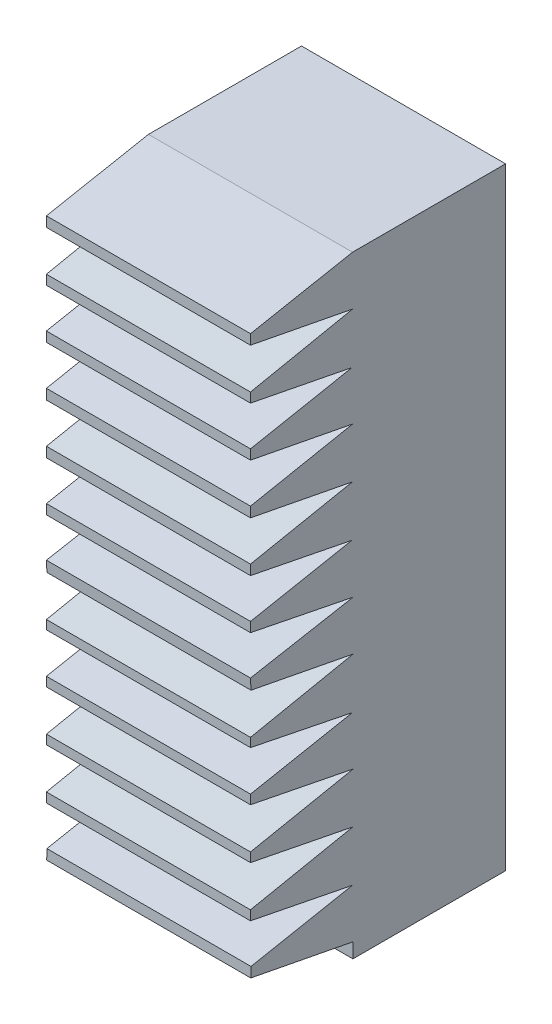
SolidWorks part; units mm, degrees
ref_plane "Alzado" through (0, 0, 0) normal (0, 0, 1) x (1, 0, 0)
ref_plane "Planta" through (0, 0, 0) normal (0, 1, 0) x (1, 0, 0)
ref_plane "Vista lateral" through (0, 0, 0) normal (1, 0, 0) x (0, 0, -1)
sketch "Croquis1" plane through (0, 0, 0) normal (0, 0, 1) x (1, 0, 0)
  line L0 (0, 0) -> (2, 0)
  line L1 (2, 0) -> (2, 6)
  line L2 (2, 6) -> (0, 6)
  line L3 (0, 6) -> (0, 0)
extrude "Saliente-Extruir1" add sketch "Croquis1" along normal blind 2.5
sketch "Croquis2" plane through (0, 0, 0) normal (1, 0, 0) x (0, 0, -1)
  line L0 (0, 6) -> (-1.5, 6)
  line L1 (-2.5, 6) -> (0, 6) construction
  line L2 (-1.5, 6) -> (-2.5, 5.8085)
  line L3 (-2.5, 6) -> (-2.5, 0) construction
  line L4 (-2.5, 5.8085) -> (-2.5, 5.7104)
  line L5 (-1.5, 5.5171) -> (-2.5, 5.3132)
  line L6 (-1.5, 5.5171) -> (-2.5, 5.7104)
  line L7 (-2.5, 5.3132) -> (-2.5, 5.2188)
  line L8 (-1.5051, 5.0236) -> (-2.5, 5.2188)
  line L9 (-1.5051, 5.0236) -> (-2.5, 4.8311)
  line L10 (-2.5, 4.8311) -> (-2.5, 4.7347)
  line L11 (-1.4991, 4.5413) -> (-2.5, 4.7347)
  line L12 (-1.4991, 4.5413) -> (-2.5, 4.3449)
  line L13 (-2.5, 4.3449) -> (-2.5, 4.2449)
  line L14 (-1.5019, 4.0514) -> (-2.5, 3.8528)
  line L15 (-1.5019, 4.0514) -> (-2.5, 4.2449)
  line L16 (-2.5, 3.8528) -> (-2.5, 3.7548)
  line L17 (-1.507, 3.5579) -> (-2.5, 3.7548)
  line L18 (-1.507, 3.5579) -> (-2.5, 3.3666)
  line L19 (-2.5, 3.3666) -> (-2.5, 3.2706)
  line L20 (-1.4953, 3.0693) -> (-2.5, 3.2706)
  line L21 (-1.4953, 3.0693) -> (-2.5, 2.8859)
  line L22 (-2.5, 2.8859) -> (-2.4953, 2.7797)
  line L23 (-1.4953, 2.5863) -> (-2.5, 2.3823)
  line L24 (-1.4953, 2.5863) -> (-2.4953, 2.7797)
  line L25 (-2.5, 2.3823) -> (-2.5, 2.2948)
  line L26 (-1.5004, 2.0928) -> (-2.5, 2.2948)
  line L27 (-1.5004, 2.0928) -> (-2.5, 1.9007)
  line L28 (-2.5, 1.9007) -> (-2.5, 1.81)
  line L29 (-1.4944, 1.6105) -> (-2.5, 1.81)
  line L30 (-1.4944, 1.6105) -> (-2.5, 1.4097)
  line L31 (-2.5, 1.4097) -> (-2.5, 1.319)
  line L32 (-1.4972, 1.1207) -> (-2.5, 0.9187)
  line L33 (-1.4972, 1.1207) -> (-2.5, 1.319)
  line L34 (-2.5, 0.9187) -> (-2.5, 0.8249)
  line L35 (-1.5023, 0.6272) -> (-2.5, 0.8249)
  line L36 (-1.5023, 0.6272) -> (-2.4953, 0.4358)
  line L37 (-2.4953, 0.4358) -> (-2.4972, 0.3383)
  line L38 (-1.4963, 0.1449) -> (-2.4972, 0.3383)
  line L39 (-1.4963, 0.1449) -> (-1.4963, 0)
  line L40 (-2.5, 0) -> (0, 0) construction
  line L41 (-1.4963, 0) -> (-2.5626, 0)
  line L42 (-2.5626, 0) -> (-2.5626, 6)
  line L43 (-2.5626, 6) -> (-1.5, 6)
extrude "Cortar-Extruir1" cut sketch "Croquis2" along normal through all contours L43 L42 L41 L39 L38 L37 L36 L35 L34 L32 L33 L31 L30 L29 L28 L27 L26 L25 L23 L24 L22 L21 L20 L19 L18 L17 L16 L14 L15 L13 L12 L11 L10 L9 L8 L7 L5 L6 L4 L2
